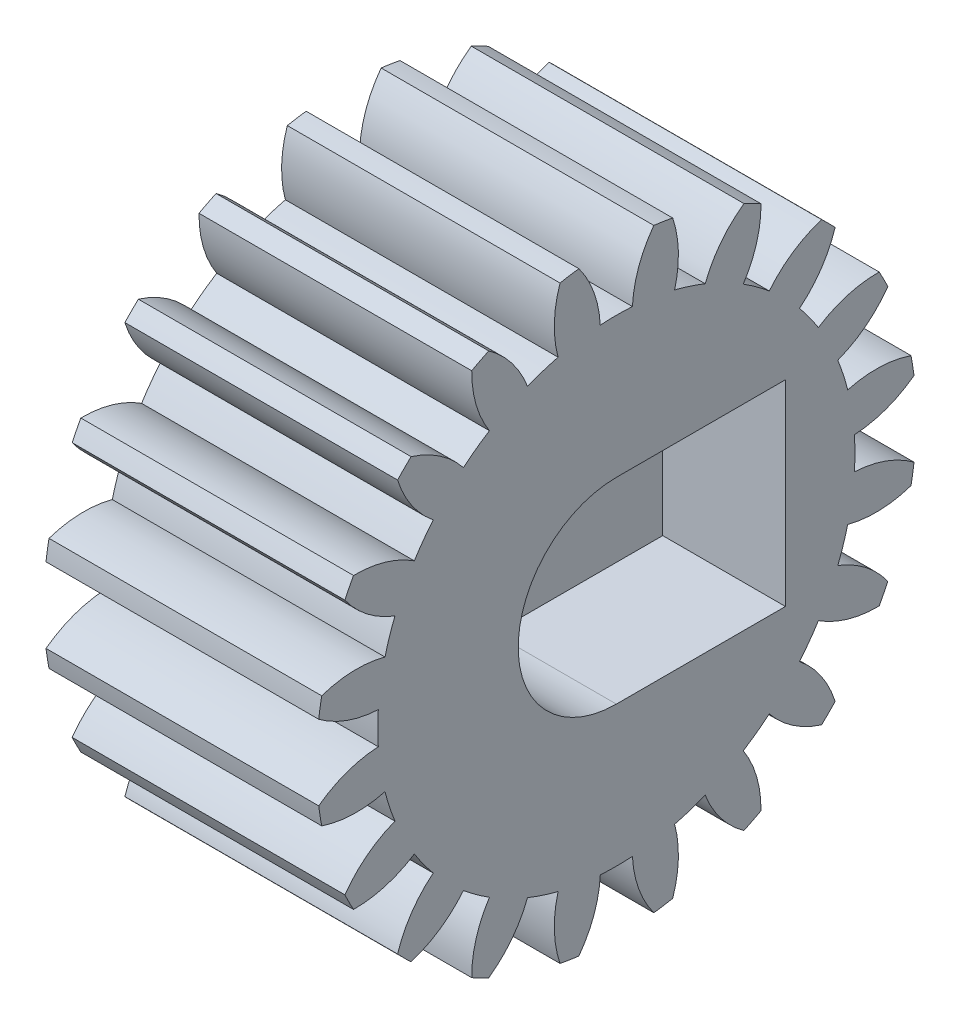
SolidWorks part; units mm, degrees
ref_plane "Plane1" through (0, 0, 0) normal (0, 0, 1) x (1, 0, 0)
ref_plane "Plane2" through (0, 0, 0) normal (0, 1, 0) x (1, 0, 0)
ref_plane "Plane3" through (0, 0, 0) normal (1, 0, 0) x (0, 0, -1)
other "Configuration Table"
sketch "HoldingSke" plane through (0, 0, 0) normal (0, 1, 0) x (1, 0, 0)
  line L0 (0, 0) -> (0.9397, -0.342)
  line L1 (-15, 0) -> (100, 0) construction
  line L2 (0, 0) -> (-2.1039, 2.3779)
  line L3 (0, 0) -> (-11.863, 4.5341)
  line L4 (0, 0) -> (8.1152, 2.9537)
  line L5 (0, 0) -> (-46.8476, -17.4728)
  line L6 (0, 0) -> (-8.2896, -5.593)
  line L7 (-2.1039, 2.3779) -> (8.6586, 51.2059)
  line L8 (-76.2, 54.61) -> (-76, 54.61)
  line L9 (-67.7845, 28.3722) -> (-49.3413, 33.142)
  line L10 (-76.2, 71.12) -> (104.1128, 71.12)
  line L11 (0, 0) -> (-10, 0)
  line L12 (-76.2, 101.6) -> (-76.162, 101.6)
  line L13 (24.9733, 27.94) -> (52.9518, 28.4284)
  line L14 (24.9733, 27.94) -> (24.9743, 27.94)
  line L15 (24.9733, 27.94) -> (100.4006, 29.5858)
  line L16 (-63.627, -1) -> (-12.827, -1)
  circle A0 centre (0, 0) radius 0.75
  circle A1 centre (0, 0) radius 8.749
  circle A2 centre (0, 0) radius 37.5
  circle A3 centre (0, 0) radius 0.75
  dimension "MHD" = 17.498
  dimension "Hub_dia" = 75
  dimension "Bore" = 1.5
  dimension "MBD" = 1.5
  dimension "Num_teeth" = 20
  dimension "Pitch" = 1
  dimension "Overall_len" = 50
  dimension "Show_teeth" = 20
  dimension "Thickness" = 10
  dimension "OAL" = 50.0001
  dimension "T_dim" = 0.2
  dimension "Ap" = 14.5
  dimension "H" = 19.05
  dimension "Pitch_radius" = 180.3128
  dimension "Width" = 10
  dimension "Backlash" = 0.038
  dimension "Addendum_fac" = 1
  dimension "Dedendum_fac" = 1.25
  dimension "Clearance_fac" = 0.25
  dimension "Dedendum_add" = 0.001
  dimension "Module" = 1
sketch "BasProSke" plane through (0, 0, 0) normal (0, 1, 0) x (1, 0, 0)
  line L0 (-10, 0) -> (60, 0) construction
  line L1 (0, 0) -> (0, 11)
  line L2 (0, 0) -> (10, 0)
  line L3 (10, 0) -> (10, 11)
  line L4 (10, 11) -> (0, 11)
  dimension "Thickness" = 10
  dimension "Diameter" = 22
revolve "Base-Revolve" add sketch "BasProSke" angle 360 about L0
sketch "TooCutSke" plane through (0, 0, 0) normal (1, 0, 0) x (0, 0, -1)
  line L1 (0, 0) -> (0, 107) construction
  line L2 (0, 0) -> (-0.8511, 9.9637) construction
  line L3 (0, 0) -> (-3.1206, 19.7028) construction
  line L4 (-0.8511, 9.9637) -> (-1.5603, 9.8514) construction
  arc A0 (0.5894, 8.7291) -> (-0.5894, 8.7291) centre (0, 0) ccw
  arc A1 (1.3917, 10.9372) -> (-1.3917, 10.9372) centre (0, 0) ccw
  circle A2 centre (0, 0) radius 10 construction
  circle A3 centre (0, 0) radius 9.6815 construction
  arc A4 (-0.5894, 8.7291) -> (-1.3917, 10.9372) centre (-4.5843, 8.5273) ccw
  arc A5 (1.3917, 10.9372) -> (0.5894, 8.7291) centre (4.5843, 8.5273) ccw
  dimension "Root_dia" = 17.498
  dimension "Overcut_dia" = 22.0508
  dimension "Pitch_dia" = 20
  dimension "Base_dia" = 19.363
  dimension "Flank_rad" = 4
  dimension "Half_ang" = 9
  dimension "Half_CT" = 0.7181
extrude "ToothCut" cut sketch "TooCutSke" along normal through all
fillet "Breaks" [suppressed] radius 0.02
fillet "RootFillets" [suppressed] radius 0.251
pattern_circular "TeethCuts" count 20 every 18 about axis through (-10, 0, 0) along (1, 0, 0) of "ToothCut", "RootFillets", "Breaks"
sketch "HubNeaOneSke" plane through (0, 0, 0) normal (-1, 0, 0) x (0, 0, 1)
  circle A0 centre (0, 0) radius 8.749
  dimension "Diameter" = 17.498
extrude "HubNearOne" [suppressed] add sketch "HubNeaOneSke" along normal blind 40.0001
sketch "HubNeaBotSke" plane through (0, 0, 0) normal (-1, 0, 0) x (0, 0, 1)
  circle A0 centre (0, 0) radius 8.749
  dimension "Diameter" = 17.498
extrude "HubNearBoth" [suppressed] add sketch "HubNeaBotSke" along normal blind 20
ref_plane "FarPln" through (10, 0, 0) normal (1, 0, 0) x (0, 0, -1)
sketch "HubFarSke" plane through (10, 0, 0) normal (1, 0, 0) x (0, 0, -1)
  circle A0 centre (0, 0) radius 8.749
  dimension "Diameter" = 17.498
extrude "HubFar" [suppressed] add sketch "HubFarSke" along normal blind 20
sketch "BorSke" plane through (0, 0, 0) normal (1, 0, 0) x (0, 0, -1)
  circle A0 centre (0, 0) radius 0.75
  dimension "Diameter" = 1.5
extrude "Bore" cut sketch "BorSke" along normal mid plane 100.0001
sketch "KeySke" plane through (0, 0, 0) normal (1, 0, 0) x (0, 0, -1)
  line L0 (-0.3, 0) -> (-0.3, 0.95)
  line L1 (-0.3, 0.95) -> (0.3, 0.95)
  line L2 (0.3, 0.95) -> (0.3, 0)
  line L3 (0, 0) -> (0, 34) construction
  line L4 (-0.3, 0) -> (0.3, 0)
  dimension "Offset" = 0.95
  dimension "Width" = 0.6
extrude "Keyway" [suppressed] cut sketch "KeySke" along normal mid plane 100.0001
pattern_circular "Keyway2" [suppressed] count 2 every 90 about axis through (-10, 0, 0) along (1, 0, 0)
sketch "Sketch1" plane through (10, 0, 0) normal (1, 0, 0) x (0, 0, -1)
  line L0 (0, 3.6) -> (6.2, 3.6)
  line L1 (0, -3.6) -> (6.2, -3.6)
  line L2 (6.2, -3.6) -> (6.2, 3.6)
  arc A1 (0, 3.6) -> (0, -3.6) centre (0, 0) ccw
  dimension "D1" = 7.2
  dimension "D2" = 6.2
  dimension "D3" = 6.2
extrude "Cut-Extrude1" cut sketch "Sketch1" against normal blind 4.5
sketch "Sketch2" plane through (0, 0, 0) normal (-1, 0, 0) x (0, 0, 1)
  circle A0 centre (0, 0) radius 1.3
  dimension "D1" = 2.6
extrude "Cut-Extrude2" cut sketch "Sketch2" against normal blind 10
sketch "Sketch3" plane through (0, 0, 0) normal (-1, 0, 0) x (0, 0, 1)
  circle A0 centre (0, 0) radius 3
  dimension "D1" = 6
extrude "Cut-Extrude3" cut sketch "Sketch3" against normal blind 0.5
equation "' \"Module@HoldingSke\" = 6.35"
equation "' \"Num_teeth@HoldingSke\" = 12"
equation "' \"Ap@HoldingSke\" =  20"
equation "' \"Ap@HoldingSke\" = 20"
equation "' \"Width@HoldingSke\" = 0.5 * 25.4"
equation "' \"Hub_dia@HoldingSke\"= 1 * 25.4"
equation "' \"Hub_dia@HoldingSke\" = 1 * 25.4"
equation "' \"Overall_len@HoldingSke\" = 1.0 * 25.4"
equation "' \"Bore@HoldingSke\" = 0.75 * 25.4"
equation "' \"T_dim@HoldingSke\" = 0.1 * 25.4"
equation "' \"Width@KeySke\" = 0.25 * 25.4"
equation "' \"Show_teeth@HoldingSke\" = 13"
equation "' \"Backlash@HoldingSke\" = 0.009 * 25.4"
equation "' \"Addendum_fac@HoldingSke\" = 1.0"
equation "' \"Dedendum_fac@HoldingSke\" = 1.25"
equation "' \"Dedendum_add@HoldingSke\" = 0.00005 * 25.4"
equation "' \"Clearance_fac@HoldingSke\" = 0.25"
equation "\"Pitch@HoldingSke\" = 1 / \"Module@HoldingSke\""
equation "\"Overcut_dia@TooCutSke\" = (\"Num_teeth@HoldingSke\" + 2 * \"Addendum_fac@HoldingSke\") / \"Pitch@HoldingSke\" + 0.002 * 25.4"
equation "\"Pitch_dia@TooCutSke\" = \"Num_teeth@HoldingSke\" / \"Pitch@HoldingSke\""
equation "\"Base_dia@TooCutSke\" = \"Num_teeth@HoldingSke\" / \"Pitch@HoldingSke\" * cos((\"Ap@HoldingSke\"  * 3.14159265 / 180))"
equation "\"Root_dia@TooCutSke\" = (\"Num_teeth@HoldingSke\" + 2) / \"Pitch@HoldingSke\" - 2 * (\"Addendum_fac@HoldingSke\" + \"Dedendum_fac@HoldingSke\") / \"Pitch@HoldingSke\" - \"Dedendum_add@HoldingSke\" * 2"
equation "\"Half_ang@TooCutSke\" = 180 / \"Num_teeth@HoldingSke\""
equation "\"Half_CT@TooCutSke\" = \"Num_teeth@HoldingSke\" / \"Pitch@HoldingSke\" * sin((3.14159265 / 2 / \"Num_teeth@HoldingSke\")) / 2 - 7 * \"Backlash@HoldingSke\" / 4"
equation "\"Flank_rad@TooCutSke\" = \"Num_teeth@HoldingSke\" / \"Pitch@HoldingSke\" / 5"
equation "\"Radius@RootFillets\" = \"Clearance_fac@HoldingSke\" / \"Pitch@HoldingSke\" + \"Dedendum_add@HoldingSke\""
equation "\"Break_rad@Breaks\" = 0.02 / \"Pitch@HoldingSke\""
equation "\"Thickness@HoldingSke\" = \"Width@HoldingSke\""
equation "\"OAL@HoldingSke\" = \"Thickness@HoldingSke\""
equation "\"MHD@HoldingSke\" = (\"Num_teeth@HoldingSke\" + 2) / \"Pitch@HoldingSke\" - 2 * (\"Addendum_fac@HoldingSke\" + \"Dedendum_fac@HoldingSke\")  / \"Pitch@HoldingSke\" - \"Dedendum_add@HoldingSke\" * 2"
equation "\"MBD@HoldingSke\" = (\"Num_teeth@HoldingSke\" + 2) / \"Pitch@HoldingSke\" - 2 * (\"Addendum_fac@HoldingSke\" + \"Dedendum_fac@HoldingSke\")  / \"Pitch@HoldingSke\" - \"Dedendum_add@HoldingSke\" * 2 - 0.002 * 25.4"
equation "\"MHD@HoldingSke\" = ((sgn( \"MHD@HoldingSke\" - \"Hub_dia@HoldingSke\" )-1)*( \"MHD@HoldingSke\" - \"Hub_dia@HoldingSke\" ))/-2+ \"Hub_dia@HoldingSke\""
equation "\"MBD@HoldingSke\" = ((sgn( \"MBD@HoldingSke\" - \"Bore@HoldingSke\" )-1)*( \"MBD@HoldingSke\" - \"Bore@HoldingSke\" ))/-2+ \"Bore@HoldingSke\""
equation "\"OAL@HoldingSke\" = ((sgn( \"OAL@HoldingSke\" - \"Overall_len@HoldingSke\" )+1)*( \"OAL@HoldingSke\" - \"Overall_len@HoldingSke\" ))/2 + \"Overall_len@HoldingSke\" + 0.000002 * 25.4"
equation "\"Num_teeth@TeethCuts\" = int( \"Show_teeth@HoldingSke\" ) + 1"
equation "\"Num_teeth@TeethCuts\" = ((sgn( \"Num_teeth@TeethCuts\" - \"Num_teeth@HoldingSke\" )-1)*( \"Num_teeth@TeethCuts\" - \"Num_teeth@HoldingSke\" ))/-2+ \"Num_teeth@HoldingSke\""
equation "\"Num_teeth@TeethCuts\" = ((sgn( \"Num_teeth@TeethCuts\" - 2.0)+1)*( \"Num_teeth@TeethCuts\" - 2.0))/2 +2.0"
equation "\"Angle@TeethCuts\" = 360.0 / \"Num_teeth@HoldingSke\""
equation "\"Diameter@BasProSke\" = (\"Num_teeth@HoldingSke\" + 2 * \"Addendum_fac@HoldingSke\") / \"Pitch@HoldingSke\""
equation "\"Thickness@BasProSke\"  = \"Thickness@HoldingSke\""
equation "' \"Fillet_rad@BasProSke\" =  \"Thickness@HoldingSke\" * 0.05"
equation "' \"Fillet_rad@BasProSke\" = \"Thickness@HoldingSke\" * 0.05"
equation "\"MHD@HoldingSke\" = ((sgn( \"MHD@HoldingSke\" - \"Root_dia@TooCutSke\" )-1)*( \"MHD@HoldingSke\" - \"Root_dia@TooCutSke\" ))/-2+ \"Root_dia@TooCutSke\""
equation "\"Diameter@HubNeaOneSke\" = \"MHD@HoldingSke\""
equation "\"Length@HubNearOne\" = \"OAL@HoldingSke\" - \"Thickness@BasProSke\""
equation "\"Diameter@HubNeaBotSke\" = \"MHD@HoldingSke\""
equation "\"Length@HubNearBoth\" = ( \"OAL@HoldingSke\" - \"Thickness@BasProSke\" ) / 2.0"
equation "\"Thickness@FarPln\" = \"Thickness@BasProSke\""
equation "\"Diameter@HubFarSke\" = \"MHD@HoldingSke\""
equation "\"Length@HubFar\" = ( \"OAL@HoldingSke\" - \"Thickness@BasProSke\" ) / 2.0"
equation "\"Diameter@BorSke\" = \"MBD@HoldingSke\""
equation "\"D1@Bore\" = \"OAL@HoldingSke\" * 2.0"
equation "\"D1@Keyway\" = \"OAL@HoldingSke\" * 2.0"
equation "\"Offset@KeySke\" = \"T_dim@HoldingSke\" + \"MBD@HoldingSke\" / 2.0"
